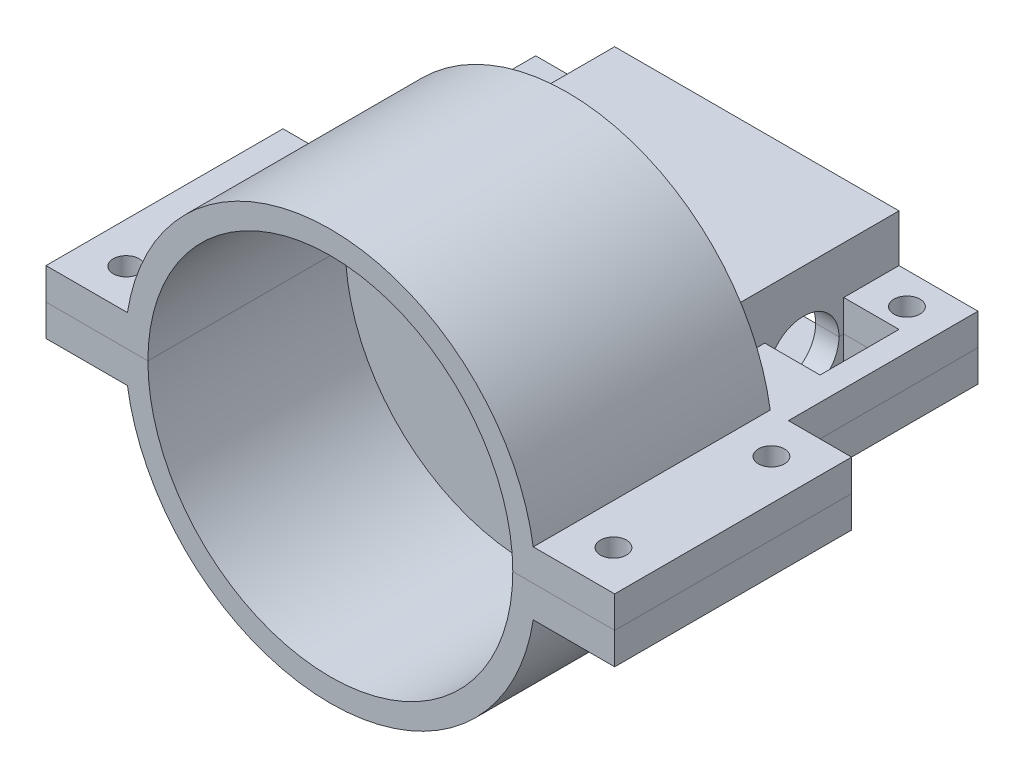
SolidWorks part; units mm, degrees
material "ABS"
ref_plane "正面" through (0, 0, 0) normal (0, 0, 1) x (1, 0, 0)
ref_plane "平面" through (0, 0, 0) normal (0, 1, 0) x (1, 0, 0)
ref_plane "右側面" through (0, 0, 0) normal (1, 0, 0) x (0, 0, -1)
sketch "ｽｹｯﾁ1" plane through (0, 0, 0) normal (0, 0, 1) x (1, 0, 0)
  circle A0 centre (0, 0) radius 26
  circle A1 centre (0, 0) radius 23.1
  dimension "D1" = 46.2
  dimension "D2" = 52
extrude "ﾎﾞｽ - 押し出し1" add sketch "ｽｹｯﾁ1" along normal blind 25
sketch "ｽｹｯﾁ2" plane through (0, 0, 0) normal (0, 0, -1) x (-1, 0, 0)
  circle A0 centre (0, 0) radius 26
extrude "ﾎﾞｽ - 押し出し2" add sketch "ｽｹｯﾁ2" along normal blind 5
sketch "ｽｹｯﾁ3" plane through (0, 0, -5) normal (0, 0, -1) x (-1, 0, 0)
  line L1 (-15.05, -7.6) -> (15.05, -7.6)
  line L2 (-15.05, -7.6) -> (-15.05, 7.6)
  line L3 (-15.05, 7.6) -> (15.05, 7.6)
  line L4 (15.05, -7.6) -> (15.05, 7.6)
  line L5 (-15.05, -7.6) -> (15.05, 7.6) construction
  line L6 (-15.05, 7.6) -> (15.05, -7.6) construction
  line L7 (-18, -10) -> (18, -10)
  line L8 (-18, -10) -> (-18, 10)
  line L9 (-18, 10) -> (18, 10)
  line L10 (18, -10) -> (18, 10)
  line L11 (-18, -10) -> (18, 10) construction
  line L12 (-18, 10) -> (18, -10) construction
  point P0 (0, 0)
  point P6 (0, 0)
  dimension "D1" = 15.2
  dimension "D2" = 30.1
  dimension "D3" = 20
  dimension "D4" = 36
extrude "ﾎﾞｽ - 押し出し3" add sketch "ｽｹｯﾁ3" along normal blind 24
sketch "ｽｹｯﾁ4" plane through (18, 0, 0) normal (1, 0, 0) x (0, 0, -1)
  line L0 (0, 0) -> (29, 0) construction
  line L1 (29, 10) -> (29, -10) construction
  circle A0 centre (16.9, 0) radius 4.5
  dimension "D2" = 9
  dimension "D1" = 12.1
extrude "ｶｯﾄ - 押し出し1" cut sketch "ｽｹｯﾁ4" against normal up to surface (36 mm away) up to face at (-18, 0, -17)
ref_plane "平面1" through (0, 0, 0) normal (0, 1, 0) x (1, 0, 0)
sketch "ｽｹｯﾁ5" plane through (0, 0, 0) normal (0, 1, 0) x (1, 0, 0)
  line L0 (18, 5) -> (28, 5)
  line L1 (28, 5) -> (28, 29)
  line L2 (28, 29) -> (18, 29)
  line L3 (18, 29) -> (18, 5)
  line L4 (25, -25) -> (36, -25)
  line L5 (36, -25) -> (36, 5)
  line L6 (36, 5) -> (25, 5)
  line L8 (25, 5) -> (25, -25)
  line L9 (0, 0) -> (0, 29) construction
  line L10 (-18, 29) -> (18, 29) construction
  line L11 (-36, 5) -> (-25, 5)
  line L12 (-36, -25) -> (-36, 5)
  line L13 (-25, -25) -> (-36, -25)
  line L14 (-25, 5) -> (-25, -25)
  line L15 (-28, 29) -> (-18, 29)
  line L16 (-28, 5) -> (-28, 29)
  line L17 (-18, 5) -> (-28, 5)
  line L18 (-18, 29) -> (-18, 5)
  line L19 (26, -25) -> (26, 5) construction
  dimension "D1" = 10
  dimension "D2" = 11
  dimension "D3" = 1
extrude "ﾎﾞｽ - 押し出し4" add sketch "ｽｹｯﾁ5" along normal blind 4 and the other way blind 4 contours L0 L8 L4 L5 L6 | L2 L3 L0 L1 | L18 L15 L16 L11 L17 | L14 L11 L12 L13
sketch "ｽｹｯﾁ6" plane through (0, 4, 0) normal (0, 1, 0) x (1, 0, 0)
  line L0 (23, 29) -> (23, 5) construction
  line L1 (28, 29) -> (18, 29) construction
  line L2 (18, 5) -> (25.6905, 5) construction
  line L3 (30.8452, -25) -> (30.8452, 5) construction
  line L4 (25.6905, -25) -> (36, -25) construction
  line L5 (28, 5) -> (36, 5) construction
  line L6 (18, 22) -> (25, 22)
  line L7 (18, 29) -> (18, 18.9616) construction
  line L8 (25, 22) -> (25, 12)
  line L9 (25, 12) -> (18, 12)
  line L10 (18, 14.8384) -> (18, 5) construction
  line L11 (18, 12) -> (18, 22)
  line L12 (0, 0) -> (0, 29) construction
  line L13 (-18, 29) -> (18, 29) construction
  line L14 (-25, 12) -> (-18, 12)
  line L15 (-25, 22) -> (-25, 12)
  line L16 (-18, 22) -> (-25, 22)
  line L17 (-18, 12) -> (-18, 22)
  circle A0 centre (23, 25) radius 1.65
  circle A2 centre (30.8452, 0) radius 1.65
  circle A3 centre (30.8452, -20) radius 1.65
  circle A4 centre (-30.8452, -20) radius 1.65
  circle A5 centre (-30.8452, 0) radius 1.65
  circle A7 centre (-23, 25) radius 1.65
  dimension "D5" = 3.3
  dimension "D1" = 4
  dimension "D2" = 7
  dimension "D3" = 5
  dimension "D4" = 5
  dimension "D6" = 7
  dimension "D7" = 10
extrude "ｶｯﾄ - 押し出し2" cut sketch "ｽｹｯﾁ6" against normal up to next
split "部品分割1" trim tools "平面1" bodies to split 106 resulting bodies 107 108
